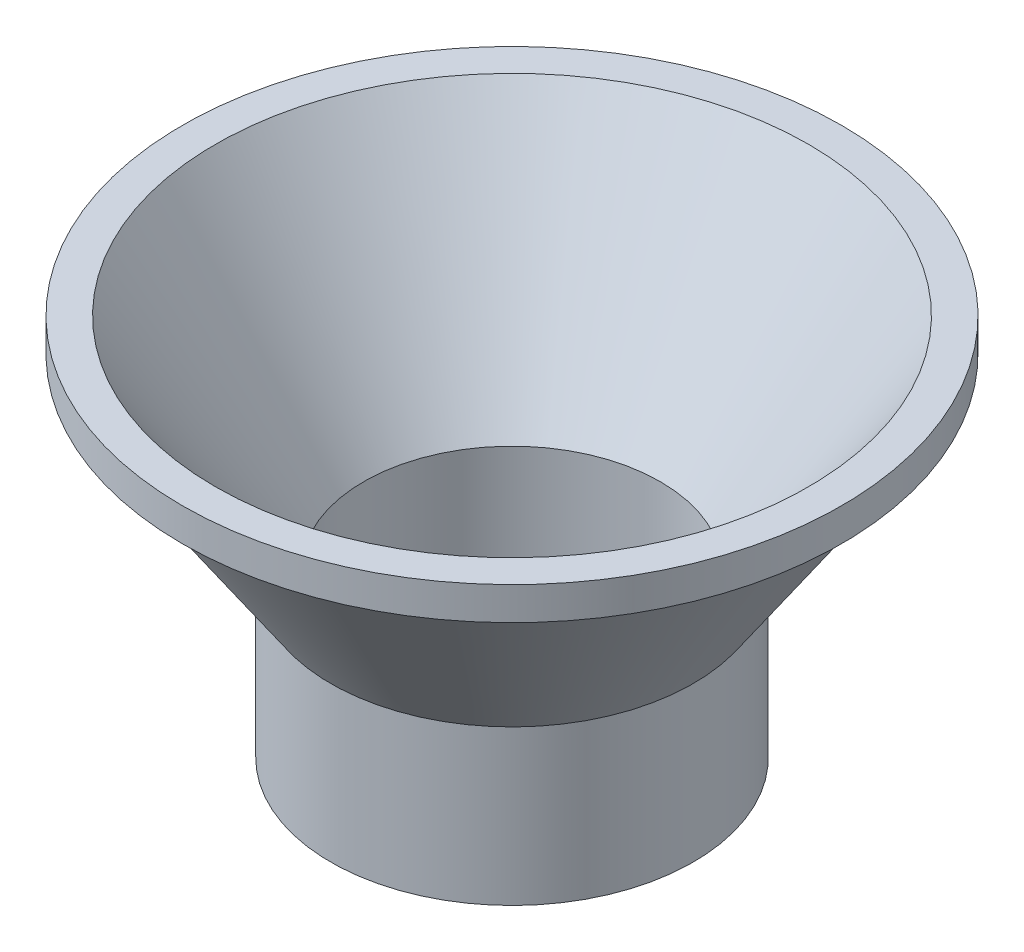
SolidWorks part; units mm, degrees
ref_plane "Front Plane" through (0, 0, 0) normal (0, 0, 1) x (1, 0, 0)
ref_plane "Top Plane" through (0, 0, 0) normal (0, 1, 0) x (1, 0, 0)
ref_plane "Right Plane" through (0, 0, 0) normal (1, 0, 0) x (0, 0, -1)
sketch "Sketch1" plane through (0, 0, 0) normal (0, 0, 1) x (1, 0, 0)
  line L0 (-9, 0) -> (-9, -10)
  line L1 (-9, 0) -> (-18, 13.2288)
  line L2 (-18, 13.2288) -> (-20, 13.2288)
  line L3 (0, 0) -> (0, 17.3566) construction
  point P0 (-9, 0)
  dimension "D1" = 9
  dimension "D2" = 10
  dimension "D3" = 16
  dimension "D4" = 9
  dimension "D5" = 2
revolve "Revolve-Thin3" add sketch "Sketch1" angle 360 about L3
